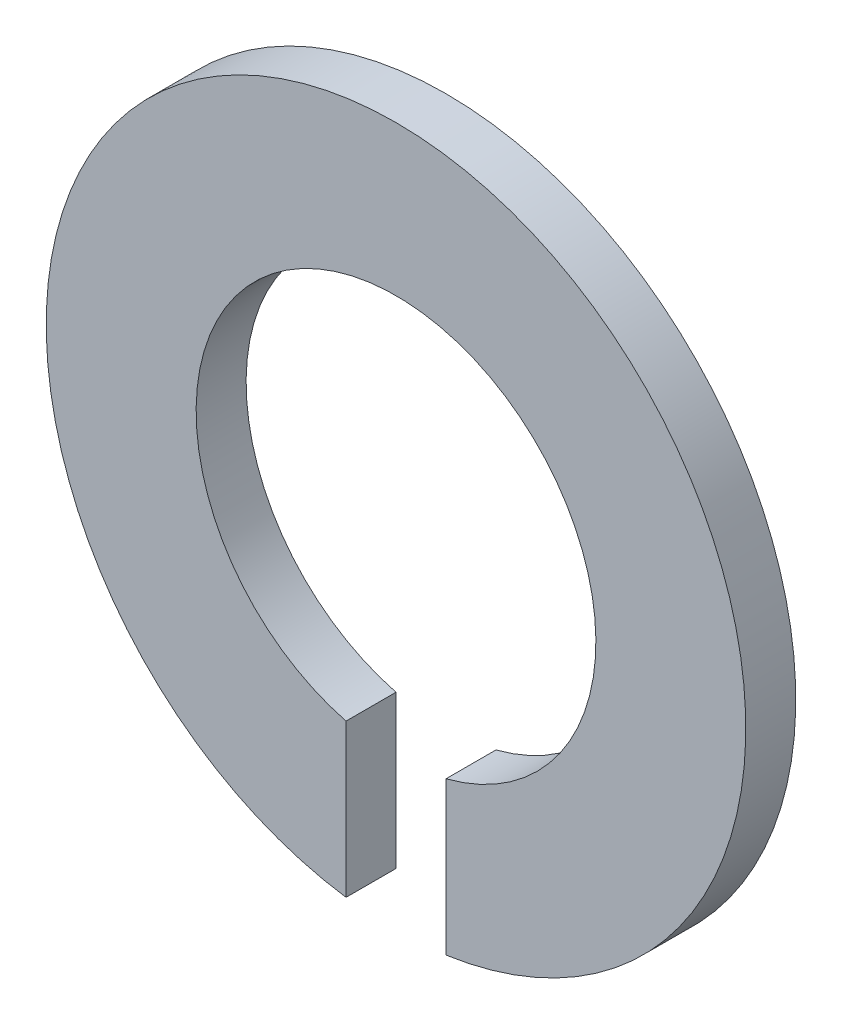
SolidWorks part; units mm, degrees
ref_plane "Plan de face" through (0, 0, 0) normal (0, 0, 1) x (1, 0, 0)
ref_plane "Plan de dessus" through (0, 0, 0) normal (0, 1, 0) x (1, 0, 0)
ref_plane "Plan de droite" through (0, 0, 0) normal (1, 0, 0) x (0, 0, -1)
sketch "Esquisse2" plane through (0, 0, 0) normal (0, 0, 1) x (1, 0, 0)
  line L0 (0, 0) -> (0, -1.75) construction
  line L2 (-0.5, -3.4641) -> (-0.5, -1.9365)
  line L4 (0.5, -3.4641) -> (0.5, -1.9365)
  arc A0 (0.5, -3.4641) -> (-0.5, -3.4641) centre (0, 0) ccw
  arc A1 (0.5, -1.9365) -> (-0.5, -1.9365) centre (0, 0) ccw
  dimension "D1" = 7
  dimension "D2" = 4
  dimension "D3" = 0.5
  dimension "D4" = 1
extrude "Boss.-Extru.2" add sketch "Esquisse2" along normal blind 0.5
